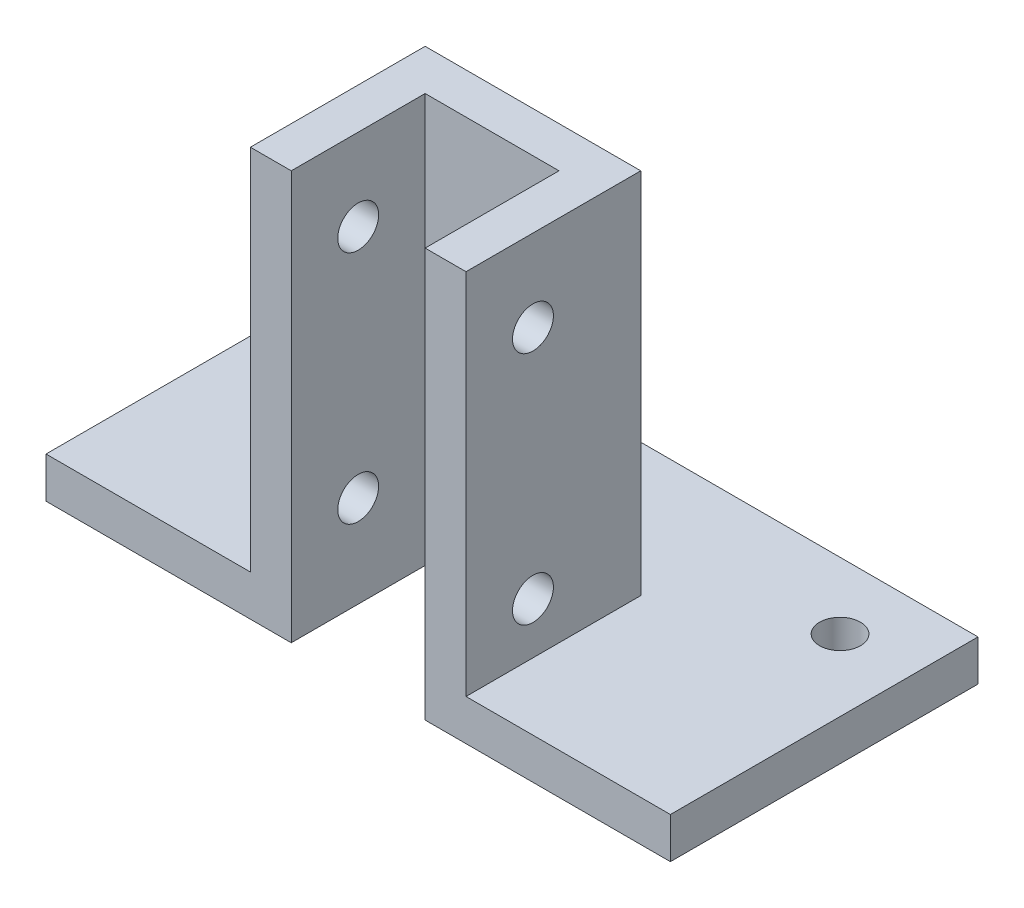
SolidWorks part; units mm, degrees
ref_plane "Front Plane" through (0, 0, 0) normal (0, 0, 1) x (1, 0, 0)
ref_plane "Top Plane" through (0, 0, 0) normal (0, 1, 0) x (1, 0, 0)
ref_plane "Right Plane" through (0, 0, 0) normal (1, 0, 0) x (0, 0, -1)
sketch "Sketch1" plane through (0, 0, 0) normal (0, 1, 0) x (1, 0, 0)
  line L1 (-6.55, -2) -> (6.55, -2)
  line L2 (-6.55, -2) -> (-6.55, 2)
  line L3 (-6.55, 2) -> (6.55, 2)
  line L4 (6.55, -2) -> (6.55, 2)
  line L5 (-6.55, -2) -> (6.55, 2) construction
  line L6 (-6.55, 2) -> (6.55, -2) construction
  line L7 (-6.55, 2) -> (-10.55, 2)
  line L8 (-6.55, 2) -> (-6.55, -15.1)
  line L9 (-6.55, -15.1) -> (-10.55, -15.1)
  line L10 (-10.55, 2) -> (-10.55, -15.1)
  line L11 (6.55, 2) -> (10.55, 2)
  line L12 (6.55, 2) -> (6.55, -15.1)
  line L13 (6.55, -15.1) -> (10.55, -15.1)
  line L14 (10.55, 2) -> (10.55, -15.1)
  point P0 (0, 0)
  point P12 (-6.55, -1.5312)
  point P13 (-6.55, 3.8279)
  dimension "D1" = 13.1
  dimension "D2" = 4
  dimension "D3" = 4
  dimension "D4" = 13.1
  dimension "D5" = 4
extrude "Boss-Extrude1" add sketch "Sketch1" along normal blind 40 contours L7 L10 L9 L8 L2 | L1 L4 L3 L2 | L14 L11 L4 L12 L13
sketch "Sketch2" plane through (0, 0, 0) normal (0, -1, 0) x (1, 0, 0)
  line L1 (10.55, 15.1) -> (30.55, 15.1)
  line L2 (10.55, 15.1) -> (10.55, -15)
  line L3 (10.55, -15) -> (30.55, -15)
  line L4 (30.55, 15.1) -> (30.55, -15)
  line L5 (-10.55, 15.1) -> (-30.55, 15.1)
  line L6 (-10.55, 15.1) -> (-10.55, -15)
  line L7 (-10.55, -15) -> (-30.55, -15)
  line L8 (-30.55, 15.1) -> (-30.55, -15)
  line L9 (10.55, -15) -> (-10.55, -15)
  line L10 (10.55, -15) -> (10.55, -2)
  line L11 (10.55, -2) -> (-10.55, -2)
  line L12 (-10.55, -15) -> (-10.55, -2)
  point P12 (-10.55, -10.1707)
  line M10 (-10.55, -2) -> (10.55, -2)
  line M11 (10.55, -2) -> (10.55, 15.1)
  line M17 (-10.55, 15.1) -> (-10.55, -2)
  dimension "D1" = 20
  dimension "D2" = 13
extrude "Boss-Extrude2" add sketch "Sketch2" against normal blind 4 contours L4 L1 L2 L3 M11 | L9 L2 L6 M10 | L5 L8 L7 L6 M17
sketch "Sketch3" plane through (0, 4, 0) normal (0, 1, 0) x (1, 0, 0)
  line L0 (0, 2) -> (0, 15) construction
  line L1 (-10.55, 2) -> (10.55, 2) construction
  line L2 (-30.55, 15) -> (30.55, 15) construction
  line L3 (0, 8.5) -> (30.55, 8.5) construction
  line L4 (30.55, -15.1) -> (30.55, 15) construction
  line L5 (0, 8.5) -> (-30.55, 8.5) construction
  line L6 (-30.55, -15.1) -> (-30.55, 15) construction
  circle A0 centre (-23.55, 8.5) radius 2
  circle A1 centre (23.55, 8.5) radius 2
  dimension "D3" = 4
  dimension "D1" = 7
  dimension "D2" = 7
extrude "Cut-Extrude1" cut sketch "Sketch3" against normal through all
sketch "Sketch4" plane through (-10.55, 0, 0) normal (-1, 0, 0) x (0, 0, 1)
  line L0 (8.55, 40) -> (8.55, 4) construction
  line L1 (15.1, 4) -> (-2, 4) construction
  line L4 (2, 0) -> (15.1, 0)
  line L5 (15.1, 0) -> (15.1, 40)
  line L6 (15.1, 40) -> (2, 40)
  line L7 (2, 40) -> (2, 0)
  line L8 (2, 0) -> (15.1, 0) construction
  line L9 (15.1, 0) -> (15.1, 40) construction
  line L10 (15.1, 40) -> (2, 40) construction
  line L11 (2, 40) -> (2, 0) construction
  circle A0 centre (8.55, 9) radius 2
  circle A1 centre (8.55, 32) radius 2
  dimension "D2" = 4
  dimension "D3" = 8
  dimension "D4" = 5
  dimension "D1" = 0
extrude "Cut-Extrude2" cut sketch "Sketch4" against normal through all
